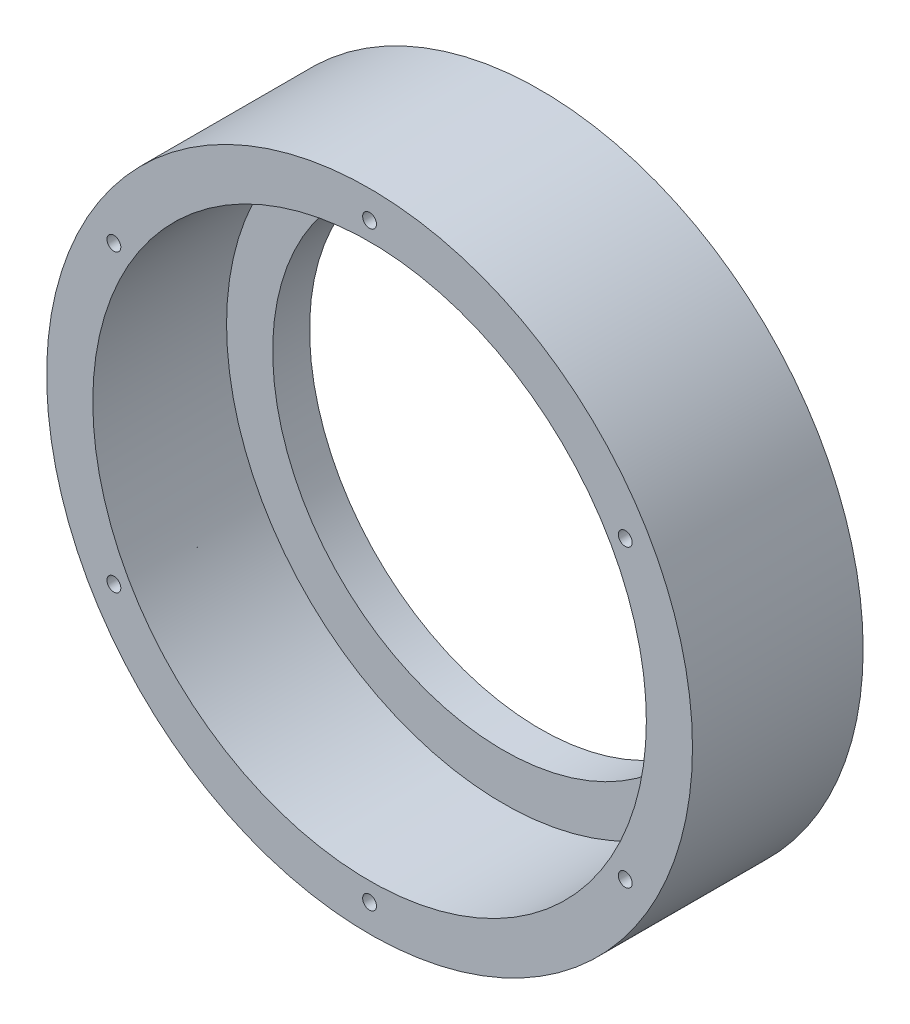
SolidWorks part; units mm, degrees
ref_plane "Front Plane" through (0, 0, 0) normal (0, 0, 1) x (1, 0, 0)
ref_plane "Top Plane" through (0, 0, 0) normal (0, 1, 0) x (1, 0, 0)
ref_plane "Right Plane" through (0, 0, 0) normal (1, 0, 0) x (0, 0, -1)
sketch "Sketch1" plane through (0, 0, 0) normal (0, 0, 1) x (1, 0, 0)
  circle A0 centre (0, 0) radius 50
  circle A1 centre (0, 0) radius 60
  dimension "D1" = 100
  dimension "D2" = 120
extrude "Boss-Extrude1" add sketch "Sketch1" along normal blind 8
sketch "Sketch2" plane through (0, 0, 8) normal (0, 0, 1) x (1, 0, 0)
  circle A0 centre (0, 0) radius 60
  circle A1 centre (0, 0) radius 70
  dimension "D1" = 140
extrude "Boss-Extrude2" add sketch "Sketch2" along normal blind 29 separate body
sketch "Sketch3" plane through (0, 0, 8) normal (0, 0, -1) x (-1, 0, 0)
  circle A0 centre (0, 0) radius 64 construction
  circle A1 centre (0, 64) radius 1.5
  dimension "D1" = 128
  dimension "D2" = 3
extrude "Cut-Extrude2" cut sketch "Sketch3" against normal blind 37
sketch "Sketch4" plane through (0, 0, 8) normal (0, 0, -1) x (-1, 0, 0)
  circle A0 centre (0, 64) radius 2.75
extrude "Cut-Extrude3" cut sketch "Sketch4" against normal blind 3
pattern_circular "CirPattern1" count 6 every 60 about axis through (0, 0, 0) along (0, 0, 1) of "Cut-Extrude3", "Cut-Extrude2"
sketch "Sketch7" plane through (0, 0, 8) normal (0, 0, -1) x (-1, 0, 0)
  circle A0 centre (0, 0) radius 70
  circle A1 centre (0, 0) radius 60
  circle A2 centre (0, 64) radius 2.75
  circle A3 centre (-55.4256, 32) radius 2.75
  circle A4 centre (-55.4256, -32) radius 2.75
  circle A5 centre (0, -64) radius 2.75
  circle A6 centre (55.4256, -32) radius 2.75
  circle A7 centre (55.4256, 32) radius 2.75
extrude "Boss-Extrude3" add sketch "Sketch7" along normal blind 8
